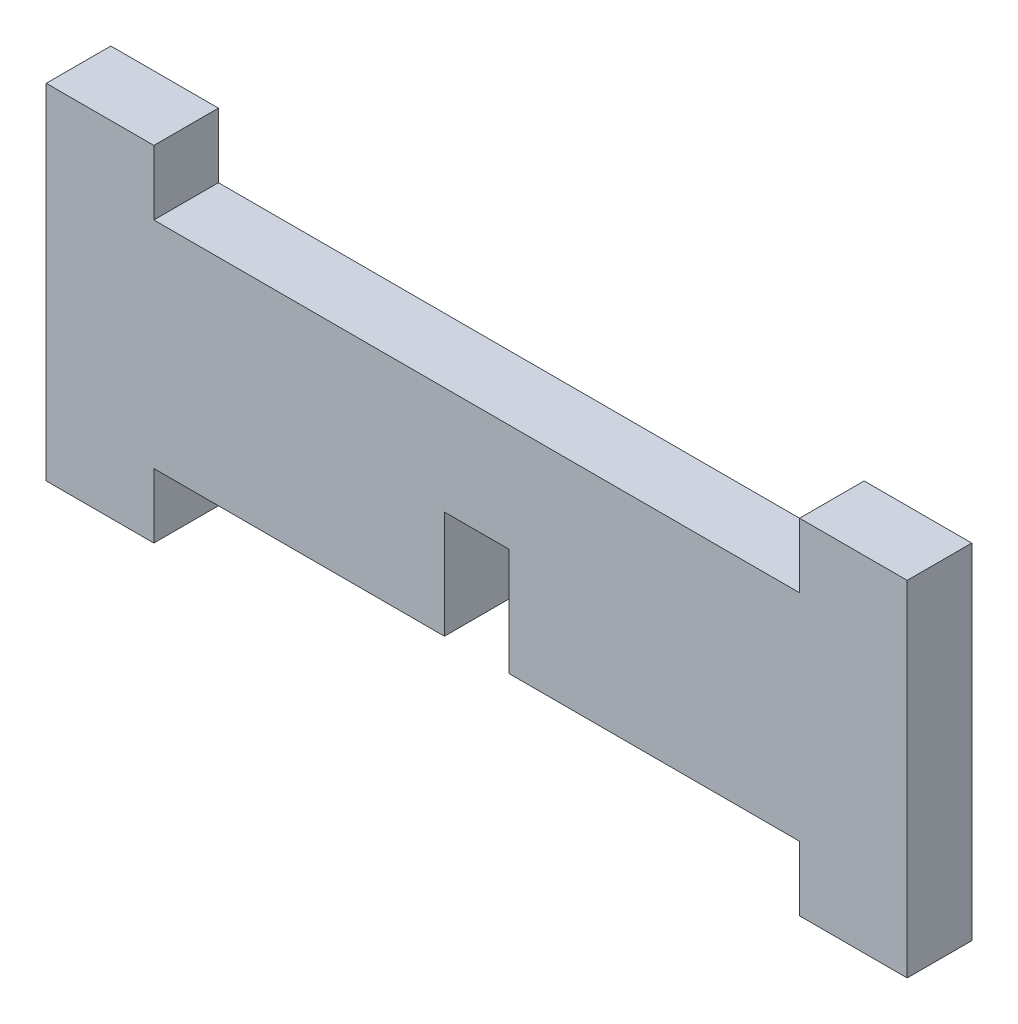
SolidWorks part; units mm, degrees
ref_plane "Alzado" through (0, 0, 0) normal (0, 0, 1) x (1, 0, 0)
ref_plane "Planta" through (0, 0, 0) normal (0, 1, 0) x (1, 0, 0)
ref_plane "Vista lateral" through (0, 0, 0) normal (1, 0, 0) x (0, 0, -1)
sketch "Croquis1" plane through (0, 0, 0) normal (0, 0, 1) x (1, 0, 0)
  line L0 (-39.5604, -10.4852) -> (-39.5604, -26.4852)
  line L1 (-39.5604, -26.4852) -> (-34.5604, -26.4852)
  line L2 (-34.5604, -26.4852) -> (-34.5604, -23.4852)
  line L3 (-34.5604, -23.4852) -> (-21.0604, -23.4852)
  line L4 (-21.0604, -23.4852) -> (-21.0604, -18.4852)
  line L5 (-21.0604, -18.4852) -> (-18.0604, -18.4852)
  line L6 (-18.0604, -18.4852) -> (-18.0604, -23.4852)
  line L7 (-18.0604, -23.4852) -> (-4.5604, -23.4852)
  line L8 (-4.5604, -23.4852) -> (-4.5604, -26.4852)
  line L9 (-4.5604, -26.4852) -> (0.4396, -26.4852)
  line L10 (0.4396, -26.4852) -> (0.4396, -10.4852)
  line L11 (0.4396, -10.4852) -> (-4.5604, -10.4852)
  line L12 (-4.5604, -10.4852) -> (-4.5604, -13.4852)
  line L13 (-4.5604, -13.4852) -> (-34.5604, -13.4852)
  line L14 (-34.5604, -13.4852) -> (-34.5604, -10.4852)
  line L15 (-34.5604, -10.4852) -> (-39.5604, -10.4852)
extrude "Saliente-Extruir1" add sketch "Croquis1" along normal blind 3
